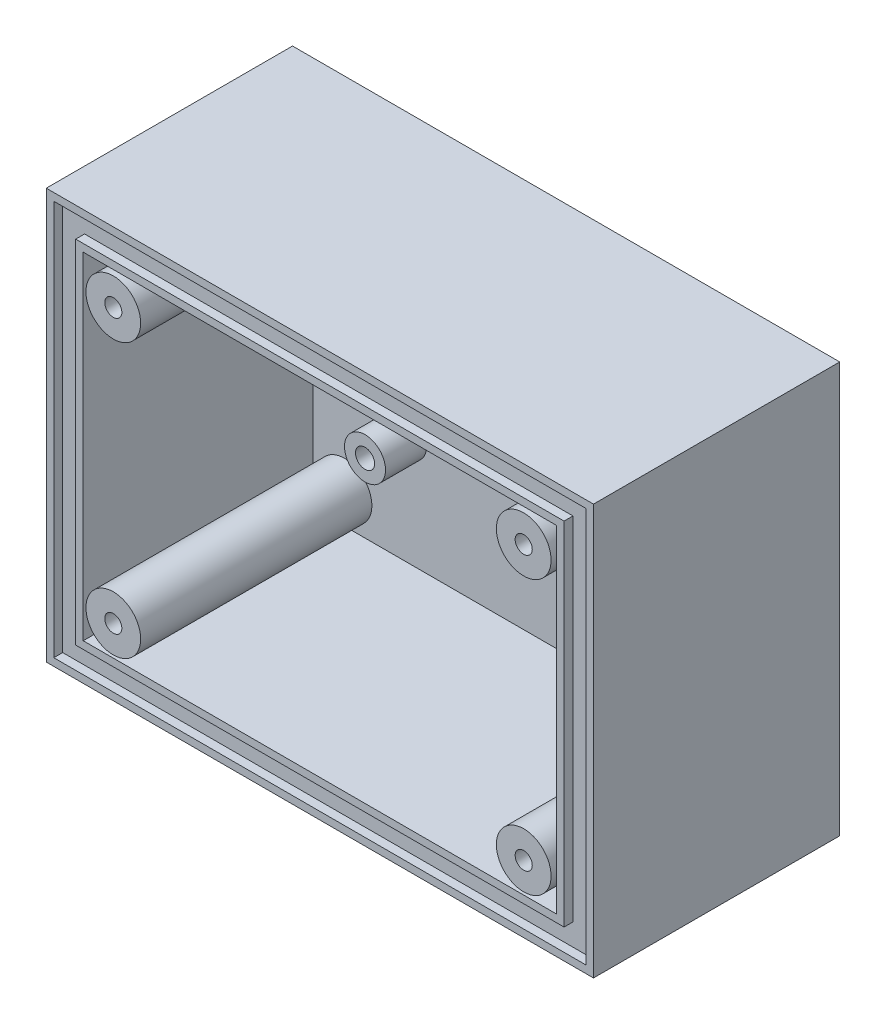
SolidWorks part; units mm, degrees
ref_plane "Front Plane" through (0, 0, 0) normal (0, 0, 1) x (1, 0, 0)
ref_plane "Top Plane" through (0, 0, 0) normal (0, 1, 0) x (1, 0, 0)
ref_plane "Right Plane" through (0, 0, 0) normal (1, 0, 0) x (0, 0, -1)
other "Configuration Table"
sketch "Sketch2" plane through (0, 0, 0) normal (0, 0, 1) x (1, 0, 0)
  line L1 (-40, -30) -> (40, -30)
  line L2 (-40, -30) -> (-40, 30)
  line L3 (-40, 30) -> (40, 30)
  line L4 (40, -30) -> (40, 30)
extrude "Floor" add sketch "Sketch2" along normal blind 2.4 from offset 0
sketch "Sketch3" plane through (0, 0, 0) normal (0, 0, 1) x (1, 0, 0)
  line L1 (-40, -30) -> (40, -30)
  line L2 (-40, -30) -> (-40, 30)
  line L3 (-40, 30) -> (40, 30)
  line L4 (40, -30) -> (40, 30)
  line L5 (-34.6, -24.6) -> (34.6, -24.6)
  line L6 (-34.6, -24.6) -> (-34.6, 24.6)
  line L7 (-34.6, 24.6) -> (34.6, 24.6)
  line L8 (34.6, -24.6) -> (34.6, 24.6)
extrude "Lower_walls" add sketch "Sketch3" along normal blind 32.3 from offset 2.4
sketch "Sketch4" plane through (0, 0, 0) normal (0, 0, 1) x (1, 0, 0)
  line L1 (-40, -30) -> (40, -30)
  line L2 (-40, -30) -> (-40, 30)
  line L3 (-40, 30) -> (40, 30)
  line L4 (40, -30) -> (40, 30)
  line L5 (-38.9, -28.9) -> (38.9, -28.9)
  line L6 (-38.9, -28.9) -> (-38.9, 28.9)
  line L7 (-38.9, 28.9) -> (38.9, 28.9)
  line L8 (38.9, -28.9) -> (38.9, 28.9)
extrude "Outer_groove_lip" add sketch "Sketch4" along normal blind 1.3 from offset 34.7
sketch "Sketch5" plane through (0, 0, 0) normal (0, 0, 1) x (1, 0, 0)
  line L1 (-35.7, -25.7) -> (35.7, -25.7)
  line L2 (-35.7, -25.7) -> (-35.7, 25.7)
  line L3 (-35.7, 25.7) -> (35.7, 25.7)
  line L4 (35.7, -25.7) -> (35.7, 25.7)
  line L5 (-34.6, -24.6) -> (34.6, -24.6)
  line L6 (-34.6, -24.6) -> (-34.6, 24.6)
  line L7 (-34.6, 24.6) -> (34.6, 24.6)
  line L8 (34.6, -24.6) -> (34.6, 24.6)
extrude "Inner_groove_lip" add sketch "Sketch5" along normal blind 1.3 from offset 34.7
sketch "Sketch6" plane through (0, 0, 0) normal (0, 0, 1) x (1, 0, 0)
  circle A0 centre (-30, -20) radius 4
  circle A1 centre (-30, -20) radius 1.25
extrude "Screw_boss" add sketch "Sketch6" along normal blind 33.8 from offset 2.4
sketch "Sketch7" plane through (0, 0, 0) normal (0, 0, 1) x (1, 0, 0)
  circle A0 centre (-30, 20) radius 4
  circle A1 centre (-30, 20) radius 1.25
extrude "Boss-Extrude6" add sketch "Sketch7" along normal blind 33.8 from offset 2.4
sketch "Sketch8" plane through (0, 0, 0) normal (0, 0, 1) x (1, 0, 0)
  circle A0 centre (30, -20) radius 4
  circle A1 centre (30, -20) radius 1.25
extrude "Boss-Extrude7" add sketch "Sketch8" along normal blind 33.8 from offset 2.4
sketch "Sketch9" plane through (0, 0, 0) normal (0, 0, 1) x (1, 0, 0)
  circle A0 centre (30, 20) radius 4
  circle A1 centre (30, 20) radius 1.25
extrude "Boss-Extrude8" add sketch "Sketch9" along normal blind 33.8 from offset 2.4
sketch "Sketch10" plane through (0, 0, 0) normal (0, 0, 1) x (1, 0, 0)
  circle A0 centre (-21, -8.5) radius 3
  circle A1 centre (-21, -8.5) radius 1.4
extrude "PCB_post" add sketch "Sketch10" along normal blind 6 from offset 2.4
sketch "Sketch11" plane through (0, 0, 0) normal (0, 0, 1) x (1, 0, 0)
  circle A0 centre (-21, 8.5) radius 3
  circle A1 centre (-21, 8.5) radius 1.4
extrude "Boss-Extrude10" add sketch "Sketch11" along normal blind 6 from offset 2.4
sketch "Sketch12" plane through (0, 0, 0) normal (0, 0, 1) x (1, 0, 0)
  circle A0 centre (21, -8.5) radius 3
  circle A1 centre (21, -8.5) radius 1.4
extrude "Boss-Extrude11" add sketch "Sketch12" along normal blind 6 from offset 2.4
sketch "Sketch13" plane through (0, 0, 0) normal (0, 0, 1) x (1, 0, 0)
  circle A0 centre (21, 8.5) radius 3
  circle A1 centre (21, 8.5) radius 1.4
extrude "Boss-Extrude12" add sketch "Sketch13" along normal blind 6 from offset 2.4
